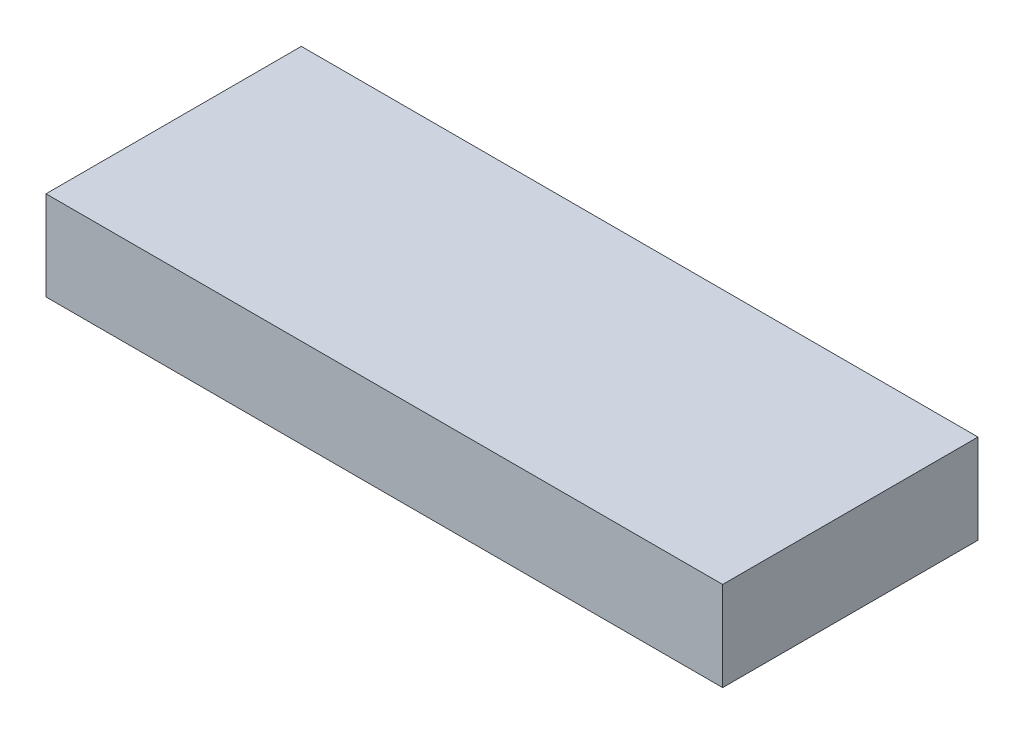
SolidWorks part; units mm, degrees
ref_plane "Front Plane" through (0, 0, 0) normal (0, 0, 1) x (1, 0, 0)
ref_plane "Top Plane" through (0, 0, 0) normal (0, 1, 0) x (1, 0, 0)
ref_plane "Right Plane" through (0, 0, 0) normal (1, 0, 0) x (0, 0, -1)
sketch "Sketch1" plane through (0, 0, 0) normal (0, 1, 0) x (1, 0, 0)
  line L1 (0, 0) -> (168.275, 0)
  line L2 (0, 0) -> (0, 63.5)
  line L3 (0, 63.5) -> (168.275, 63.5)
  line L4 (168.275, 0) -> (168.275, 63.5)
  dimension "D1" = 63.5
  dimension "D2" = 168.275
extrude "Boss-Extrude1" add sketch "Sketch1" along normal blind 22.225 contours L1 L4 L3 L2
sketch "Sketch2" plane through (0, 22.225, 0) normal (0, 1, 0) x (1, 0, 0)
  text T0 "Battery" font "Century Gothic" height in points 28
